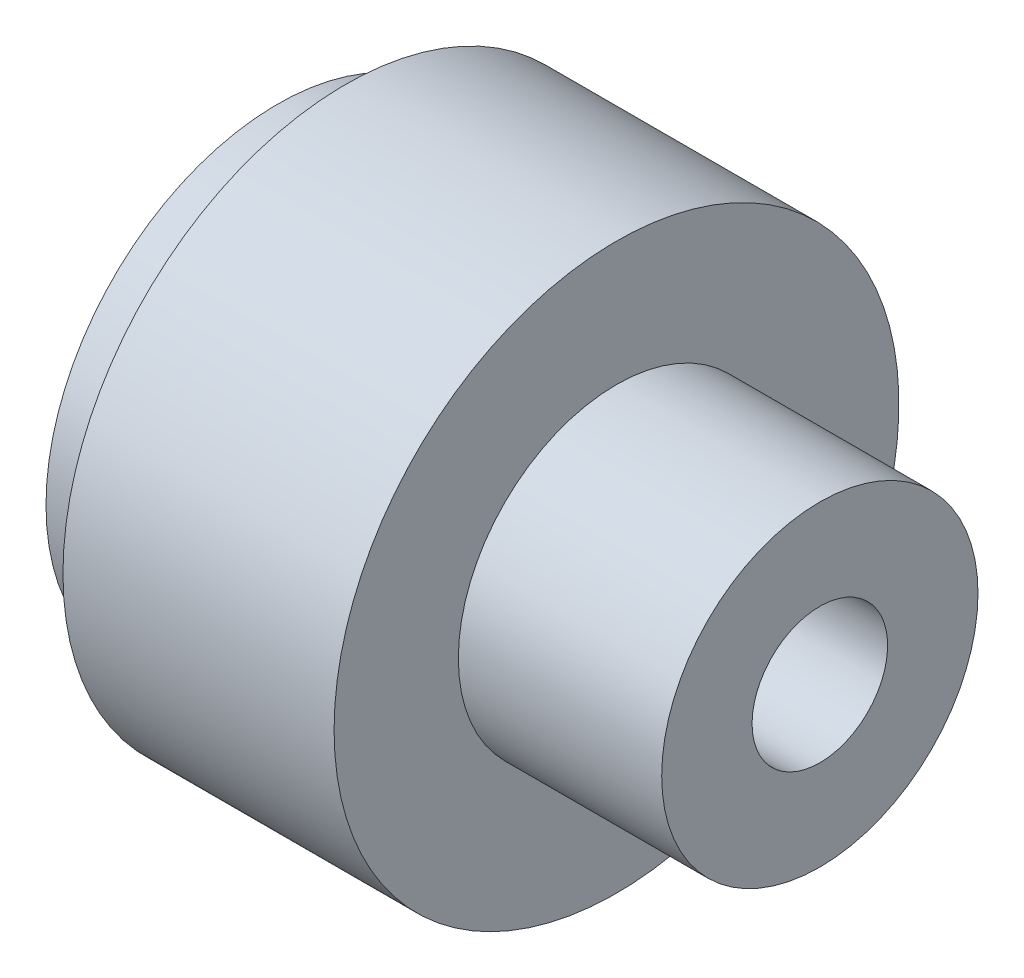
SolidWorks part; units mm, degrees
ref_plane "Plan de face" through (0, 0, 0) normal (0, 0, 1) x (1, 0, 0)
ref_plane "Plan de dessus" through (0, 0, 0) normal (0, 1, 0) x (1, 0, 0)
ref_plane "Plan de droite" through (0, 0, 0) normal (1, 0, 0) x (0, 0, -1)
sketch "Esquisse1" plane through (0, 0, 0) normal (0, 0, 1) x (1, 0, 0)
  line L0 (-21, 15.5801) -> (-21, 6.0801) construction
  line L1 (-21, 15.5801) -> (-21, -16.4092) construction
  line L2 (-9, -16.4063) -> (-9, 15.5313) construction
  line L3 (0, 15.5313) -> (0, -16.4062) construction
  line L4 (-24, -11.6563) -> (-24, 13.3301) construction
  line L5 (-14.0625, 3.0801) -> (14.625, 3.0801) construction
  line L6 (14.625, 10.0801) -> (-14.0625, 10.0801) construction
  line L7 (-14.0625, 15.5801) -> (-27.9375, 15.5801) construction
  line L8 (-14.0625, 6.0801) -> (14.625, 6.0801) construction
  line L9 (-14.0625, 13.3301) -> (-6.4375, 13.3301) construction
  line L10 (-6.4375, 8.3301) -> (-14.0625, 8.3301) construction
  line L11 (-21, 8.3301) -> (-24, 8.3301)
  line L12 (0, 6.0801) -> (-21, 6.0801)
  line L13 (-21, 6.0801) -> (-21, 8.3301)
  line L14 (-24, 8.3301) -> (-24, 13.3301)
  line L15 (-24, 13.3301) -> (-21, 13.3301)
  line L16 (-21, 13.3301) -> (-21, 15.5801)
  line L17 (-21, 15.5801) -> (-9, 15.5801)
  line L18 (-9, 15.5801) -> (-9, 10.0801)
  line L19 (-9, 10.0801) -> (0, 10.0801)
  line L20 (0, 10.0801) -> (0, 6.0801)
  line L21 (-22.8776, 10.8301) -> (-15.7634, 10.8301) construction
  point P0 (-21, 10.8301)
  point P1 (-21, 10.8301)
  point P3 (0, 0)
  dimension "D1" = 21
  dimension "D2" = 9
  dimension "D3" = 24
  dimension "D4" = 3
  dimension "D5" = 7
  dimension "D6" = 12.5
  dimension "D7" = 5
  dimension "D8" = 5
revolve "Révolution1" add sketch "Esquisse1" angle 360 about L5
